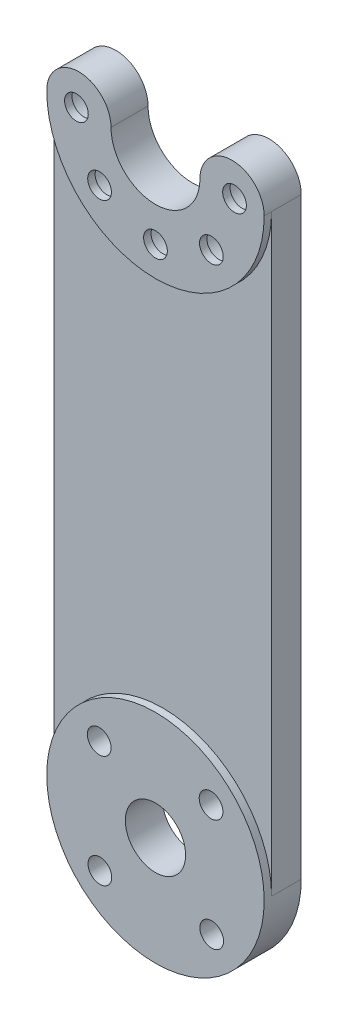
SolidWorks part; units mm, degrees
ref_plane "Plano frontal" through (0, 0, 0) normal (0, 0, 1) x (1, 0, 0)
ref_plane "Plano superior" through (0, 0, 0) normal (0, 1, 0) x (1, 0, 0)
ref_plane "Plano direito" through (0, 0, 0) normal (1, 0, 0) x (0, 0, -1)
sketch "Esboço1" plane through (0, 0, 0) normal (0, 0, 1) x (1, 0, 0)
  arc A2 (-4.5, 0) -> (4.5, 0) centre (0, 0) ccw
  arc A3 (11, 0) -> (-11, 0) centre (0, 0) cw
  arc A4 (-4, 0) -> (4, 0) centre (0, 0) ccw construction
  arc A5 (11, 0) -> (4.5, 0) centre (7.75, 0) ccw
  arc A6 (-4.5, 0) -> (-11, 0) centre (-7.75, 0) ccw
  arc A9 (-11, 0) -> (11, 0) centre (0, 0) ccw construction
  dimension "D1" = 0.5
extrude "Ressalto-extrusão1" add sketch "Esboço1" against normal offset from surface (0.75 mm away) 2
sketch "Esboço3" plane through (0, 0, -0.75) normal (0, 0, -1) x (-1, 0, 0)
  line L0 (-11, 0) -> (-11, -60)
  line L2 (11, -60) -> (11, 0)
  arc A0 (11, 0) -> (4.5, 0) centre (7.75, 0) ccw construction
  arc A1 (-4.5, 0) -> (4.5, 0) centre (0, 0) ccw construction
  arc A2 (-4.5, 0) -> (-11, 0) centre (-7.75, 0) ccw construction
  arc A3 (11, 0) -> (4.5, 0) centre (7.75, 0) ccw
  arc A4 (-4.5, 0) -> (4.5, 0) centre (0, 0) ccw
  arc A5 (-4.5, 0) -> (-11, 0) centre (-7.75, 0) ccw
  arc A9 (-11, -60) -> (11, -60) centre (0, -60) ccw
extrude "Ressalto-extrusão2" add sketch "Esboço3" along normal blind 3
hole_wizard "Rebaixo para SHCS M21" positions "Sketch1" profile "Sketch2" counterbore size "M2" standard "Ansi Metric" end condition up to next
sketch "Sketch1" plane through (0, 0, -3.75) normal (0, 0, -1) x (-1, 0, 0)
  line L0 (0, 0) -> (-8, 0) construction
  line L1 (0, 0) -> (-5.6569, -5.6569) construction
  line L2 (0, 0) -> (0, -8) construction
  line L3 (0, 0) -> (5.6569, -5.6569) construction
  line L4 (0, 0) -> (8, 0) construction
  arc A0 (-9, 0) -> (-7, 0) centre (-8, 0) ccw construction
  point P0 (-8, 0)
  point P16 (-5.6569, -5.6569)
  point P18 (0, -8)
  point P20 (5.6569, -5.6569)
  point P22 (8, 0)
  dimension "D1" = 5
sketch "Sketch2" plane through (8, 0, -3.75) normal (1, 0, 0) x (0, 1, 0)
  line L0 (0, 0) -> (0, 3.75)
  line L1 (0, 3.75) -> (1.2, 3.75)
  line L3 (1.2, 3.75) -> (1.2, 3)
  line L4 (1.2, 3) -> (2.2, 3)
  line L5 (2.2, 3) -> (2.2, 0)
  line L7 (2.2, 0) -> (0, 0)
  line L11 (0, -6.35) -> (0, 107.95) construction
  dimension "Thru Hole Dia." = 2.4
  dimension "Thru Hole Depth" = 3.75
  dimension "C'Bore Dia." = 4.4
  dimension "C'Bore Depth" = 3
sketch "Esboço4" plane through (0, 0, -0.75) normal (0, 0, 1) x (1, 0, 0)
  circle A0 centre (0, -60) radius 11
  arc A1 (-11, -60) -> (11, -60) centre (0, -60) ccw construction
extrude "Ressalto-extrusão3" add sketch "Esboço4" along normal up to surface (0.75 mm away)
sketch "Esboço5" plane through (0, 0, -3.75) normal (0, 0, -1) x (-1, 0, 0)
  circle A0 centre (0, -60) radius 3.05 construction
  circle A1 centre (0, -60) radius 3.05
extrude "Corte-extrusão1" cut sketch "Esboço5" against normal through all
hole_wizard "Rebaixo para parafuso com cabeça redonda de M21" positions "Esboço6" profile "Esboço7" counterbore size "M2" standard "DIN" end condition up to next
sketch "Esboço6" plane through (0, 0, -3.75) normal (0, 0, -1) x (-1, 0, 0)
  circle A0 centre (5.6247, -65.6888) radius 0.8 construction
  point P0 (5.6247, -65.6888)
sketch "Esboço7" plane through (-5.6247, -65.6888, -3.75) normal (1, 0, 0) x (0, 1, 0)
  line L0 (0, 0) -> (0, 3.75)
  line L1 (0, 3.75) -> (1.2, 3.75)
  line L3 (1.2, 3.75) -> (1.2, 1.4)
  line L4 (1.2, 1.4) -> (2.2, 1.4)
  line L5 (2.2, 1.4) -> (2.2, 0)
  line L7 (2.2, 0) -> (0, 0)
  line L11 (0, -6.35) -> (0, 107.95) construction
  dimension "Thru Hole Dia." = 2.4
  dimension "Thru Hole Depth" = 3.75
  dimension "C'Bore Dia." = 4.4
  dimension "C'Bore Depth" = 1.4
pattern_circular "PadrãoCircular1" count 4 over 360 about axis through (0, -60, 0) along (0, 0, 1) of "Rebaixo para parafuso com cabeça redonda de M21"
